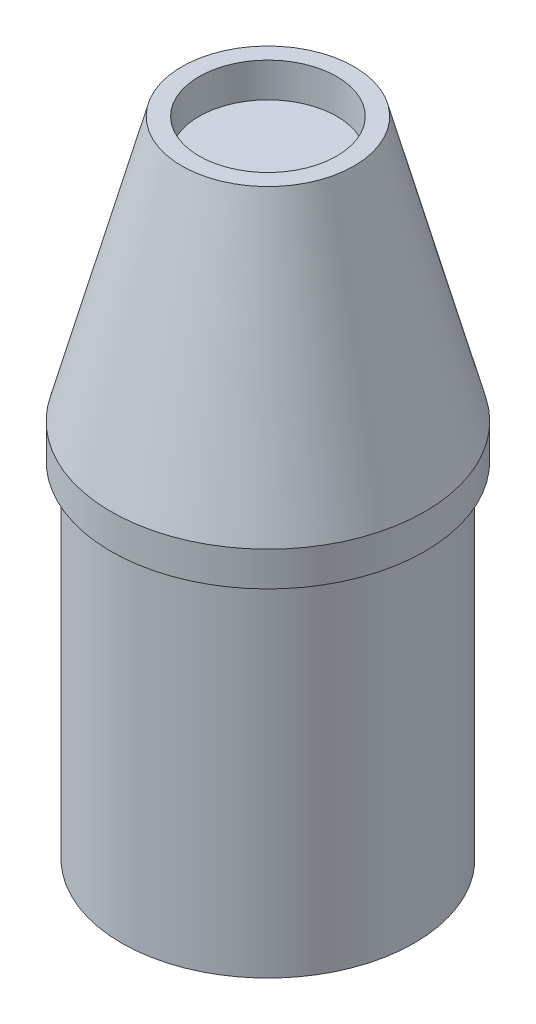
SolidWorks part; units mm, degrees
material "6061 Alloy"
ref_plane "Front Plane" through (0, 0, 0) normal (0, 0, 1) x (1, 0, 0)
ref_plane "Top Plane" through (0, 0, 0) normal (0, 1, 0) x (1, 0, 0)
ref_plane "Right Plane" through (0, 0, 0) normal (1, 0, 0) x (0, 0, -1)
sketch "Sketch1" plane through (0, 0, 0) normal (0, 0, 1) x (1, 0, 0)
  line L0 (0, -4.2497) -> (0, 107.927)
  line L1 (0, 107.927) -> (12.7, 107.927)
  line L2 (12.7, 107.927) -> (12.7, 114.277)
  line L3 (12.7, 114.277) -> (15.875, 114.277)
  line L4 (15.875, 114.277) -> (28.9179, 65.6003)
  line L5 (28.9179, 65.6003) -> (28.9179, 59.2503)
  line L6 (28.9179, 59.2503) -> (26.9875, 59.2503)
  line L7 (26.9875, 59.2503) -> (26.9875, -4.2497)
  line L8 (26.9875, -4.2497) -> (0, -4.2497)
  dimension "D1" = 28.9179
  dimension "D2" = 15
  dimension "D3" = 15.875
  dimension "D5" = 63.5
  dimension "D6" = 6.35
  dimension "D7" = 12.7
  dimension "D8" = 26.9875
revolve "Revolve1" add sketch "Sketch1" angle 360 about L0
